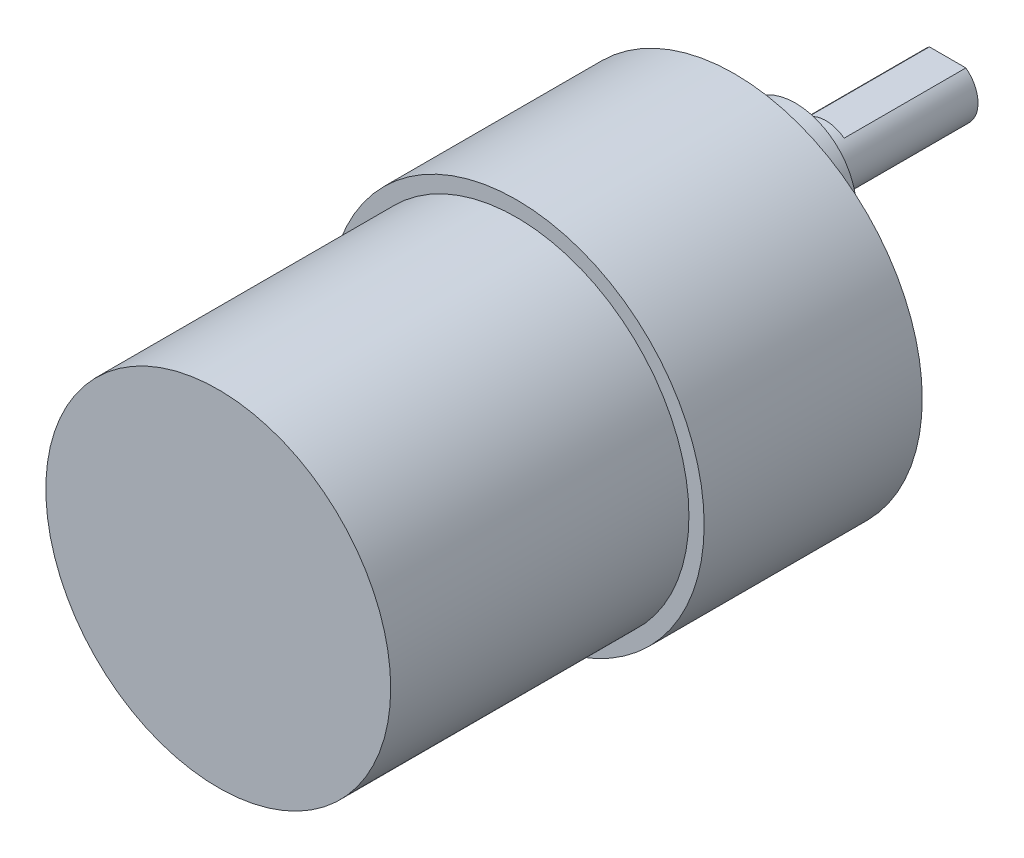
SolidWorks part; units mm, degrees
ref_plane "前视基准面" through (0, 0, 0) normal (0, 0, 1) x (1, 0, 0)
ref_plane "上视基准面" through (0, 0, 0) normal (0, 1, 0) x (1, 0, 0)
ref_plane "右视基准面" through (0, 0, 0) normal (1, 0, 0) x (0, 0, -1)
sketch "草图1" plane through (0, 0, 0) normal (0, 0, 1) x (1, 0, 0)
  circle A0 centre (0, 0) radius 18.5
extrude "凸台-拉伸1" add sketch "草图1" along normal blind 21.5 contours A0
sketch "草图2" plane through (0, 0, 21.5) normal (0, 0, 1) x (1, 0, 0)
  circle A0 centre (0, 0) radius 17
extrude "凸台-拉伸2" add sketch "草图2" along normal blind 29.4
sketch "草图3" plane through (0, 0, 0) normal (0, 0, -1) x (-1, 0, 0)
  line L0 (0, 0) -> (0, 7)
  arc A0 (-11.3605, 5.2143) -> (11.3605, 5.2143) centre (0, 7) ccw
  circle A1 centre (0, 0) radius 18.5
  arc A2 (-11.3605, 5.2143) -> (11.3605, 5.2143) centre (0, 0) ccw
extrude "切除-拉伸1" cut sketch "草图3" against normal blind 1 contours A0 A2
sketch "草图4" plane through (0, 0, 0) normal (0, 0, -1) x (-1, 0, 0)
  circle A0 centre (0, 7) radius 6
extrude "凸台-拉伸3" add sketch "草图4" along normal blind 6
sketch "草图5" plane through (0, 0, -6) normal (0, 0, -1) x (-1, 0, 0)
  circle A0 centre (0, 7) radius 3
extrude "凸台-拉伸4" add sketch "草图5" along normal blind 15
sketch "草图6" plane through (0, 0, -21) normal (0, 0, -1) x (-1, 0, 0)
  line L2 (0, 9.4) -> (1.8, 9.4)
  line L3 (0, 9.4) -> (-1.8, 9.4)
  circle A0 centre (0, 7) radius 3 construction
  arc A1 (1.8, 9.4) -> (-1.8, 9.4) centre (0, 7) ccw
extrude "切除-拉伸2" cut sketch "草图6" against normal blind 12
sketch "草图7" plane through (0, 0, 0) normal (0, 0, -1) x (-1, 0, 0)
  circle A2 centre (15.5, 0) radius 1.5
  circle A3 centre (-15.5, 0) radius 1.5
  circle A4 centre (-7.75, -13.4234) radius 1.5
  circle A6 centre (7.75, 13.4234) radius 1.5
  circle A7 centre (-7.75, 13.4234) radius 1.5
  circle A9 centre (7.75, -13.4234) radius 1.5
  point P21 (0, 0)
  dimension "D1" = 3
extrude "切除-拉伸3" cut sketch "草图7" against normal blind 5
sketch "草图8" plane through (0, 0, 0) normal (0, 0, -1) x (-1, 0, 0)
  circle A0 centre (0, -15.5) radius 2
  circle A1 centre (-13.4234, 7.75) radius 2
  circle A2 centre (13.4234, 7.75) radius 2
  point P9 (0, 0)
  dimension "D1" = 3
extrude "切除-拉伸4" cut sketch "草图8" against normal blind 1
